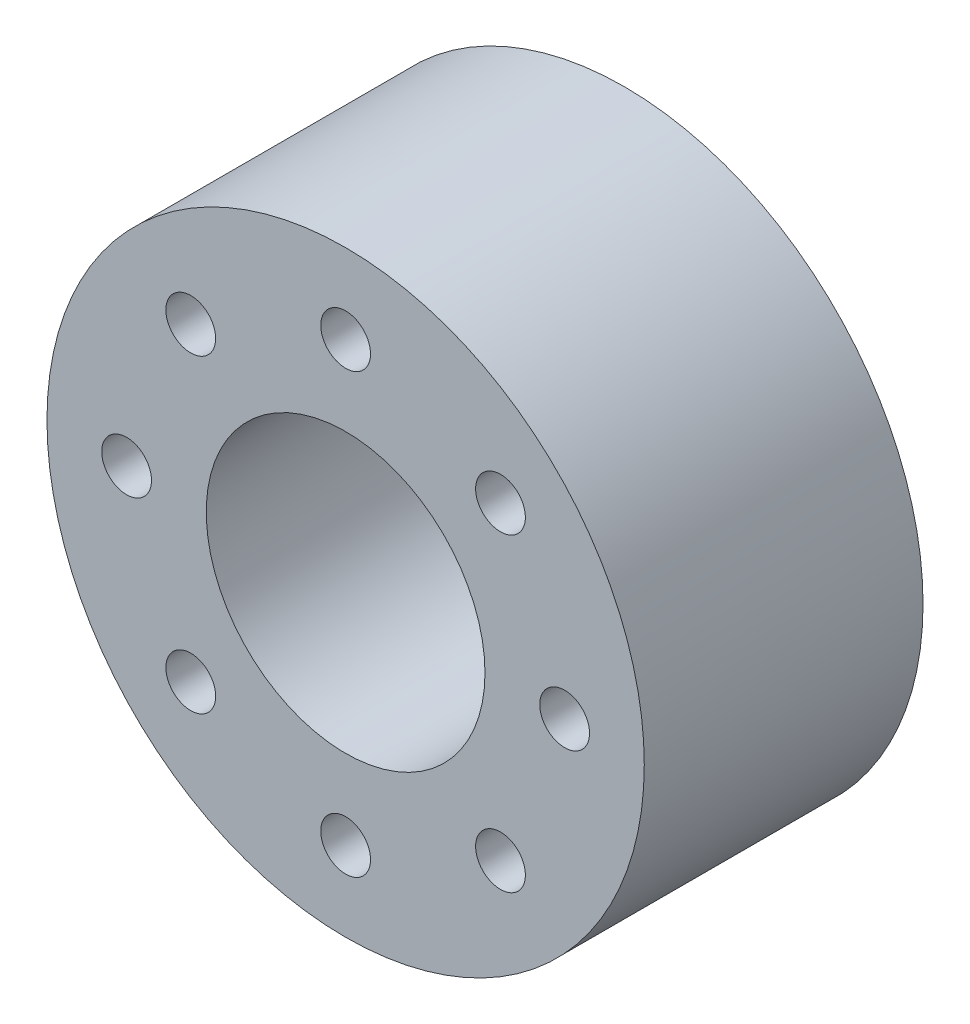
SolidWorks part; units mm, degrees
material "5052-H32"
ref_plane "Plano frontal" through (0, 0, 0) normal (0, 0, 1) x (1, 0, 0)
ref_plane "Plano superior" through (0, 0, 0) normal (0, 1, 0) x (1, 0, 0)
ref_plane "Plano direito" through (0, 0, 0) normal (1, 0, 0) x (0, 0, -1)
sketch "Esboço1" plane through (0, 0, 0) normal (0, 0, 1) x (1, 0, 0)
  circle A0 centre (0, 0) radius 7
  circle A1 centre (0, 0) radius 15
  circle A2 centre (0, 11) radius 1.25
  circle A3 centre (7.7782, 7.7782) radius 1.25
  circle A4 centre (11, 0) radius 1.25
  circle A5 centre (7.7782, -7.7782) radius 1.25
  circle A6 centre (0, -11) radius 1.25
  circle A7 centre (-7.7782, -7.7782) radius 1.25
  circle A8 centre (-11, 0) radius 1.25
  circle A9 centre (-7.7782, 7.7782) radius 1.25
  point P23 (0, 0)
  dimension "D1" = 30
  dimension "D2" = 14
  dimension "D3" = 11
  dimension "D4" = 2.5
  dimension "D5" = 8
extrude "Ressalto-extrusão1" add sketch "Esboço1" along normal mid plane 14
